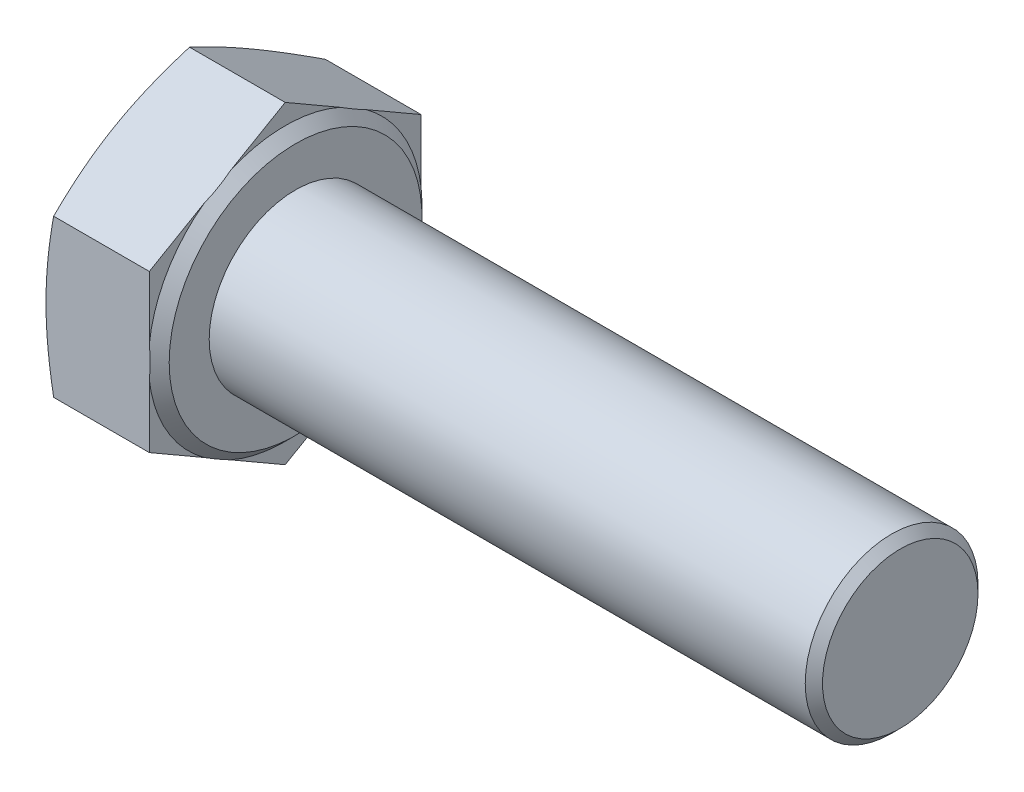
SolidWorks part; units mm, degrees
ref_plane "Front" through (0, 0, 0) normal (0, 0, 1) x (1, 0, 0)
ref_plane "Top" through (0, 0, 0) normal (0, 1, 0) x (1, 0, 0)
ref_plane "Right" through (0, 0, 0) normal (1, 0, 0) x (0, 0, -1)
other "Configuration Table"
sketch "Sketch2" plane through (0, 0, 0) normal (1, 0, 0) x (0, 0, -1)
  line L1 (7.865, -4.5409) -> (7.865, 4.5409)
  line L2 (7.865, 4.5409) -> (0, 9.0817)
  line L3 (0, 9.0817) -> (-7.865, 4.5409)
  line L4 (-7.865, 4.5409) -> (-7.865, -4.5409)
  line L5 (-7.865, -4.5409) -> (0, -9.0817)
  line L6 (0, -9.0817) -> (7.865, -4.5409)
  circle A0 centre (0, 0) radius 7.865 construction
  dimension "s" = 15.73
extrude "BaseHead" add sketch "Sketch2" along normal blind 6.58
sketch "Sketch3" plane through (0, 0, 0) normal (0, 0, 1) x (1, 0, 0)
  line L0 (6.58, 9.0817) -> (6.58, 7.315)
  line L2 (6.58, 7.315) -> (5.98, 7.915)
  line L3 (5.98, 7.915) -> (5.98, 9.0817)
  line L5 (5.98, 9.0817) -> (6.58, 9.0817)
  line L6 (-0.9571, 0) -> (7.6478, 0) construction
  line L7 (6.58, 9.0817) -> (0, 9.0817) construction
  dimension "D1" = 45
  dimension "c" = 0.6
  dimension "Dw" = 14.63
revolve "BearingFace" cut sketch "Sketch3" angle 360 about L6
sketch "Sketch4" plane through (0, 0, 0) normal (0, 0, 1) x (1, 0, 0)
  line L0 (-0.4935, 0) -> (3.5626, 0) construction
  line L2 (0, 9.0817) -> (0.4428, 9.0817)
  line L4 (0.4428, 9.0817) -> (0, 7.865)
  line L6 (0, 7.865) -> (0, 9.0817)
  line L7 (5.98, 9.0817) -> (0, 9.0817) construction
  dimension "D1" = 20
  dimension "D2" = 15.73
revolve "HeadChamfer" cut sketch "Sketch4" angle 360 about L0
sketch "Sketch5" plane through (6.58, 0, 0) normal (1, 0, 0) x (0, 0, -1)
  circle A0 centre (0, 0) radius 5
  dimension "d" = 10
extrude "BaseBody" add sketch "Sketch5" along normal blind 35
cosmetic thread "ThreadCosmetic1" [suppressed] parameters "D2"=8.376
chamfer "Chamfer1" distance 0.5 angle 45 1 edges at (41.58, 0, -5)
fillet "HeadFillet" [suppressed] radius 0.4
sketch "Sketch6" plane through (0, 0, 0) normal (0, 0, 1) x (1, 0, 0)
  line L0 (6.58, 5.812) -> (7.392, 5.812)
  line L1 (7.392, 5.812) -> (7.392, 5)
  line L2 (7.392, 5) -> (6.986, 4.2968)
  line L3 (6.986, 4.2968) -> (6.58, 5)
  line L4 (6.58, 5) -> (6.58, 5.812)
  line L5 (41.08, 5) -> (6.58, 5) construction
  line L6 (6.58, -7.315) -> (6.58, 7.315) construction
  dimension "D1" = 0.812
revolve "Cut-Revolve10" [suppressed] cut sketch "Sketch6" angle 360 about axis through (-0.9571, 0, 0) along (1, 0, 0)
pattern_linear "LPattern10" [suppressed] count 36
equation "\"D2@Sketch4\" = \"s@Sketch2\""
equation "\"D1@Chamfer1\" = 0.05 * \"d@Sketch5\""
equation "\"D1@Sketch6\" =  ( \"d@Sketch5\" - \"D2@ThreadCosmetic1\" )  / 2"
equation "\"pitch@LPattern10\" = \"D1@Sketch6\" * 1.2"
equation "\"D1@LPattern10\" = \"l@BaseBody\" / \"pitch@LPattern10\""
